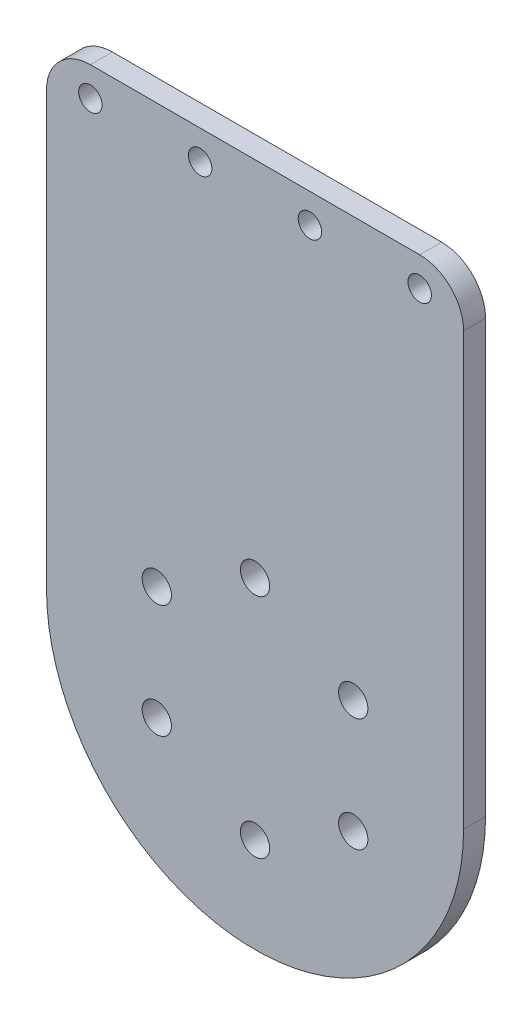
SolidWorks part; units mm, degrees
ref_plane "前基準面" through (0, 0, 0) normal (0, 0, 1) x (1, 0, 0)
ref_plane "上基準面" through (0, 0, 0) normal (0, 1, 0) x (1, 0, 0)
ref_plane "右基準面" through (0, 0, 0) normal (1, 0, 0) x (0, 0, -1)
sketch "草圖1" plane through (0, 0, 0) normal (0, 0, 1) x (1, 0, 0)
  line L8 (-28.5, 65) -> (28.5, 65)
  line L9 (-28.5, 65) -> (-28.5, 55)
  line L11 (28.5, 65) -> (28.5, 55.0205)
  line L12 (-28.5, 55) -> (-28.5, 0)
  line L13 (28.5, 55.0205) -> (28.5, 0)
  arc A0 (-21.4606, -18.7534) -> (21.4606, -18.7534) centre (0, 0) ccw
  arc A1 (-28.5, 0) -> (28.5, 0) centre (0, 0) ccw
  point P9 (0, -12.5)
  dimension "D2" = 65
  dimension "D6" = 57
extrude "填料-伸長1" add sketch "草圖1" along normal blind 3
sketch "草圖4" plane through (0, 0, 3) normal (0, 0, 1) x (1, 0, 0)
  circle A0 centre (0, -15.5) radius 2
  point P5 (0, 0)
  dimension "D4" = 4
  dimension "D1" = 15.5
extrude "除料-伸長2" cut sketch "草圖4" against normal up to next
sketch "草圖5" plane through (0, 0, 3) normal (0, 0, 1) x (1, 0, 0)
  line L0 (-997.4151, 61) -> (49002.5849, 61) construction
  line L3 (28.5, 65) -> (28.5, 0) construction
  line L4 (-28.5, 65) -> (28.5, 65) construction
  line L11 (28.5, 65) -> (-28.5, 65)
  line L12 (-28.5, 65) -> (-28.5, 0)
  line L14 (28.5, 0) -> (28.5, 65)
  line L16 (28.5, 65) -> (-28.5, 65)
  line L17 (-28.5, 65) -> (-28.5, 0)
  line L19 (28.5, 0) -> (28.5, 65)
  circle A0 centre (22.5, 61) radius 1.6
  circle A1 centre (7.5, 61) radius 1.6
  circle A2 centre (-7.5, 61) radius 1.6
  circle A3 centre (-22.5, 61) radius 1.6
  arc A5 (-28.5, 0) -> (28.5, 0) centre (0, 0) ccw
  arc A6 (-28.5, 0) -> (28.5, 0) centre (0, 0) ccw
  dimension "D2" = 3.2
  dimension "D1" = 6
  dimension "D3" = 4
  dimension "D5" = 15
  dimension "D6" = 0
  dimension "D4" = 4
extrude "除料-伸長3" cut sketch "草圖5" against normal through all flip side to cut
fillet "圓角1" radius 6 1 edges at (-28.5, 65, 1.5)
fillet "圓角2" radius 6 1 edges at (28.5, 65, 1.5)
pattern_circular "環狀複製排列1" count 6 over 360 about axis through (0, 0, 0) along (0, 0, 1) of "除料-伸長2"
